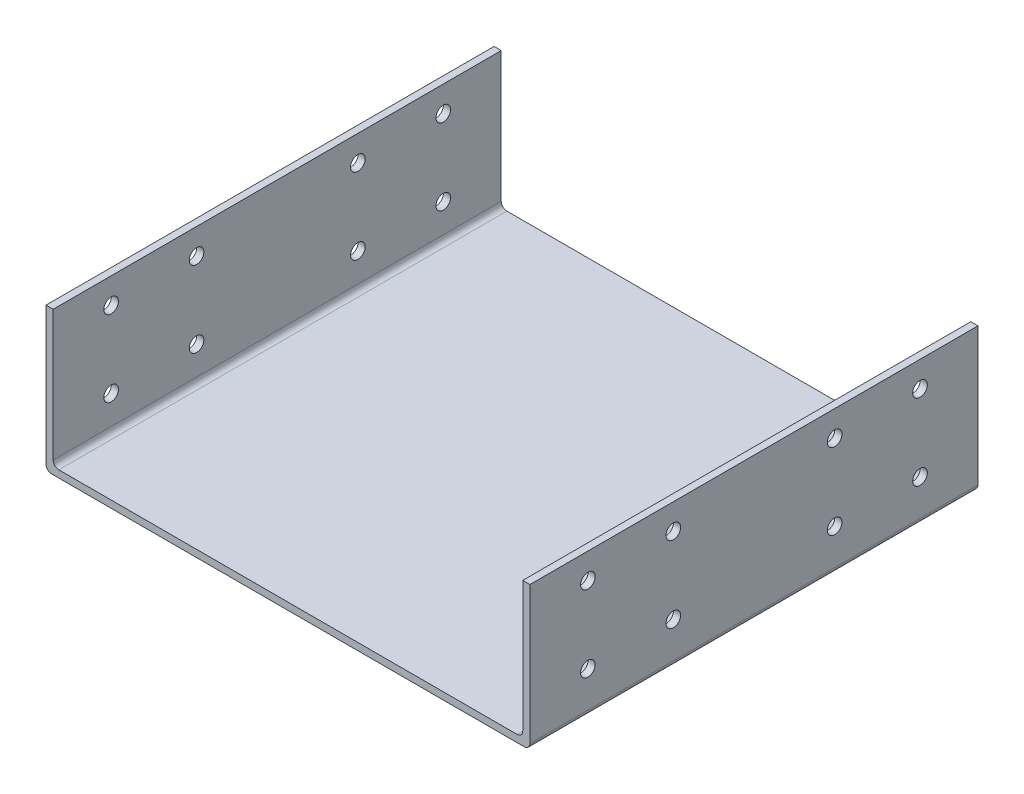
SolidWorks part; units mm, degrees
ref_plane "Front Plane" through (0, 0, 0) normal (0, 0, 1) x (1, 0, 0)
ref_plane "Top Plane" through (0, 0, 0) normal (0, 1, 0) x (1, 0, 0)
ref_plane "Right Plane" through (0, 0, 0) normal (1, 0, 0) x (0, 0, -1)
sketch "Sketch2" plane through (0, 0, 0) normal (0, 1, 0) x (1, 0, 0)
  line L1 (-85.725, -79.375) -> (85.725, -79.375)
  line L2 (-85.725, -79.375) -> (-85.725, 79.375)
  line L3 (-85.725, 79.375) -> (85.725, 79.375)
  line L4 (85.725, -79.375) -> (85.725, 79.375)
  line L5 (-85.725, -79.375) -> (85.725, 79.375) construction
  line L6 (-85.725, 79.375) -> (85.725, -79.375) construction
  point P0 (0, 0)
  dimension "D1" = 171.45
  dimension "D2" = 158.75
extrude "Boss-Extrude1" add sketch "Sketch2" along normal blind 50.8 contours L3 L4 L1 L2
sketch "Sketch3" plane through (0, 0, 79.375) normal (0, 0, 1) x (1, 0, 0)
  line L0 (-85.725, 50.8) -> (85.725, 50.8) construction
  line L1 (-83.185, 50.8) -> (83.185, 50.8)
  line L2 (-83.185, 50.8) -> (-83.185, 2.54)
  line L3 (-83.185, 2.54) -> (83.185, 2.54)
  line L4 (83.185, 50.8) -> (83.185, 2.54)
  line L5 (-85.725, 50.8) -> (-85.725, 0) construction
  line L6 (85.725, 50.8) -> (85.725, 0) construction
  line L7 (-85.725, 0) -> (85.725, 0) construction
  dimension "D1" = 2.54
  dimension "D2" = 2.54
  dimension "D3" = 2.54
extrude "Cut-Extrude1" cut sketch "Sketch3" against normal through all
fillet "Fillet1" radius 2 4 edges at (-83.185, 2.54, 0) (83.185, 2.54, 0) (-85.725, 0, 0) (85.725, 0, 0)
sketch "Sketch5" plane through (85.725, 0, 0) normal (1, 0, 0) x (0, 0, -1)
  line L6 (0, 27.94) -> (0, -27.94) construction
  line L7 (-79.375, 2) -> (79.375, 2) construction
  circle A0 centre (-58.8328, 41.7129) radius 2.5908
  circle A1 centre (-58.8328, 14.7) radius 2.5908
  circle A2 centre (58.8328, 41.7129) radius 2.5908
  circle A3 centre (58.8328, 14.7) radius 2.5908
  circle A4 centre (-28.5814, 41.7129) radius 2.5865
  circle A5 centre (-28.5814, 14.7) radius 2.5865
  circle A6 centre (28.5814, 41.7129) radius 2.5908
  circle A9 centre (28.5814, 14.7) radius 2.5865
  dimension "D1" = 5.1816
  dimension "D2" = 27.0129
  dimension "D3" = 12.7
  dimension "D4" = 57.1627
  dimension "D5" = 30.2514
  dimension "D6" = 30.2514
  dimension "D7" = 5.173
extrude "Cut-Extrude2" cut sketch "Sketch5" against normal through all
